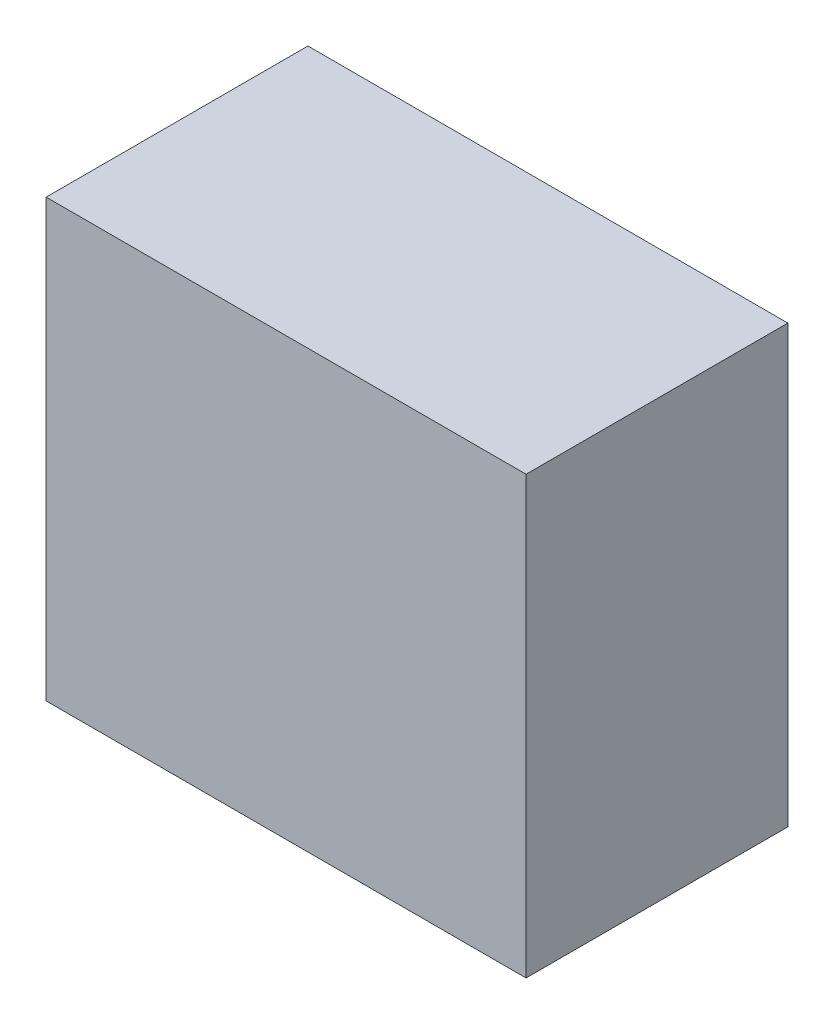
SolidWorks part; units mm, degrees
ref_plane "Alzado" through (0, 0, 0) normal (0, 0, 1) x (1, 0, 0)
ref_plane "Planta" through (0, 0, 0) normal (0, 1, 0) x (1, 0, 0)
ref_plane "Vista lateral" through (0, 0, 0) normal (1, 0, 0) x (0, 0, -1)
sketch "Croquis1" plane through (0, 0, 0) normal (0, 0, 1) x (1, 0, 0)
  line L1 (55, -50) -> (-55, -50)
  line L2 (55, -50) -> (55, 50)
  line L3 (55, 50) -> (-55, 50)
  line L4 (-55, -50) -> (-55, 50)
  line L5 (55, -50) -> (-55, 50) construction
  line L6 (55, 50) -> (-55, -50) construction
  point P0 (0, 0)
  dimension "D1" = 110
  dimension "D2" = 100
extrude "Saliente-Extruir1" add sketch "Croquis1" along normal mid plane 60
